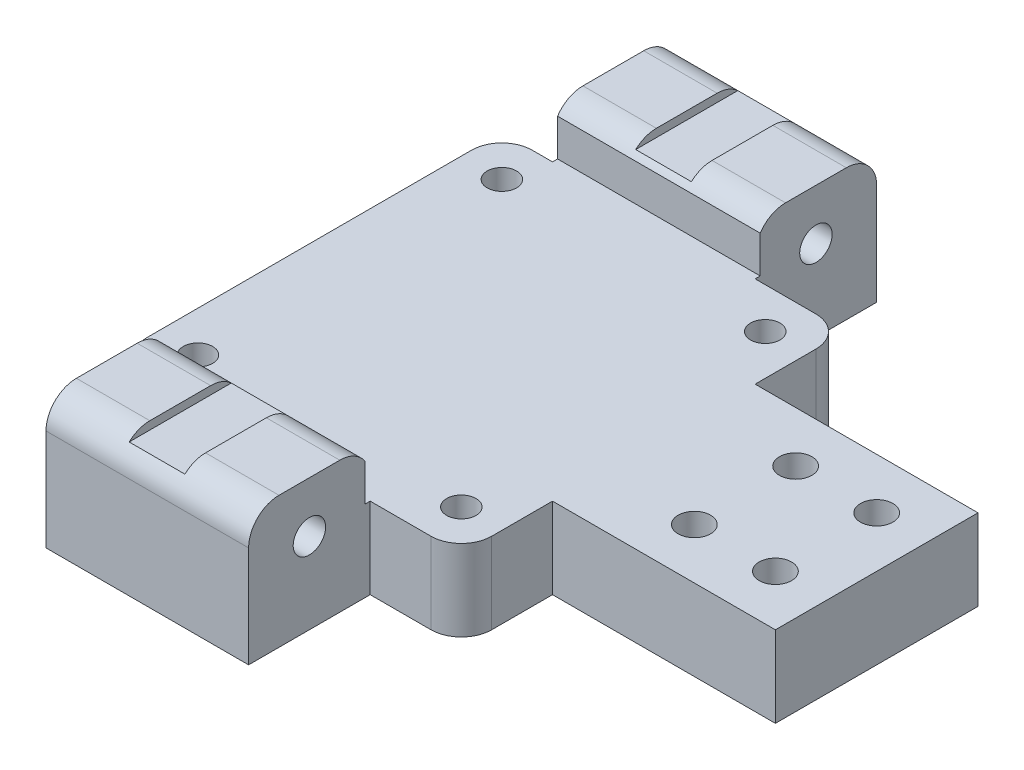
SolidWorks part; units mm, degrees
ref_plane "Front" through (0, 0, 0) normal (0, 0, 1) x (1, 0, 0)
ref_plane "Top" through (0, 0, 0) normal (0, 1, 0) x (1, 0, 0)
ref_plane "Right" through (0, 0, 0) normal (1, 0, 0) x (0, 0, -1)
sketch "Sketch1" plane through (0, 0, 0) normal (0, 1, 0) x (1, 0, 0)
  line L1 (0, 0) -> (300, 0)
  line L2 (0, 0) -> (0, -20)
  line L3 (0, -20) -> (300, -20)
  line L4 (300, 0) -> (300, -20)
  dimension "D1" = 20
  dimension "D2" = 300
extrude "Boss-Extrude1" add sketch "Sketch1" along normal blind 8
sketch "Sketch2" plane through (0, 0, 20) normal (0, 0, 1) x (1, 0, 0)
  line L0 (0, 8) -> (300, 8) construction
  line L1 (0, 0) -> (34, 0)
  line L2 (0, 0) -> (0, 8)
  line L3 (0, 8) -> (34, 8)
  line L4 (34, 0) -> (34, 8)
  line L5 (266, 8) -> (300, 8)
  line L6 (300, 0) -> (300, 8)
  line L7 (266, 0) -> (300, 0)
  line L8 (266, 0) -> (266, 8)
  dimension "D1" = 34
  dimension "D2" = 2
extrude "Boss-Extrude2" add sketch "Sketch2" along normal blind 9
sketch "Sketch3" plane through (0, 0, 0) normal (0, 0, -1) x (-1, 0, 0)
  line L0 (-300, 8) -> (0, 8) construction
  line L1 (0, 0) -> (-34, 0)
  line L2 (0, 0) -> (0, 8)
  line L3 (0, 8) -> (-34, 8)
  line L4 (-34, 0) -> (-34, 8)
  line L5 (-300, 0) -> (-300, 8)
  line L6 (-266, 8) -> (-300, 8)
  line L7 (-266, 0) -> (-266, 8)
  line L8 (-266, 0) -> (-300, 0)
  dimension "D1" = 34
  dimension "D2" = 2
extrude "Boss-Extrude3" add sketch "Sketch3" along normal blind 9
sketch "Sketch4" plane through (0, 8, 0) normal (0, 1, 0) x (1, 0, 0)
  line L0 (0, 9) -> (34, 9) construction
  line L1 (0, 9) -> (0, -29) construction
  circle A0 centre (4, 5) radius 1.45
  circle A1 centre (30, 5) radius 1.45
  circle A2 centre (30, -25) radius 1.45
  circle A3 centre (4, -25) radius 1.45
  circle A4 centre (296, -25) radius 1.45
  circle A5 centre (296, 5) radius 1.45
  circle A6 centre (270, -25) radius 1.45
  circle A7 centre (270, 5) radius 1.45
  dimension "D1" = 2.9
  dimension "D2" = 4
  dimension "D3" = 4
  dimension "D4" = 2
  dimension "D5" = 2
  dimension "D6" = 2
extrude "Cut-Extrude1" cut sketch "Sketch4" against normal through all
sketch "Sketch5" plane through (0, 0, 20) normal (0, 0, 1) x (1, 0, 0)
  line L0 (34, 8) -> (266, 8) construction
  line L1 (266, 0) -> (241, 0)
  line L2 (266, 0) -> (266, 8)
  line L3 (266, 8) -> (241, 8)
  line L4 (241, 0) -> (241, 8)
  dimension "D1" = 25
extrude "Boss-Extrude4" add sketch "Sketch5" along normal blind 17
sketch "Sketch6" plane through (0, 0, 0) normal (0, 0, -1) x (-1, 0, 0)
  line L0 (-266, 0) -> (-34, 0) construction
  line L1 (-266, 8) -> (-241, 8)
  line L2 (-266, 8) -> (-266, 0)
  line L3 (-266, 0) -> (-241, 0)
  line L4 (-241, 8) -> (-241, 0)
  dimension "D1" = 25
extrude "Boss-Extrude5" add sketch "Sketch6" along normal blind 17
sketch "Sketch7" plane through (0, 8, 0) normal (0, 1, 0) x (1, 0, 0)
  line L0 (266, -37) -> (241, -37) construction
  line L1 (259, -29) -> (249, -29)
  line L2 (259, -29) -> (259, 9)
  line L3 (259, 9) -> (249, 9)
  line L4 (249, -29) -> (249, 9)
  line L5 (241, -37) -> (241, -20) construction
  dimension "D1" = 10
  dimension "D2" = 38
  dimension "D3" = 8
  dimension "D4" = 8
extrude "Cut-Extrude2" cut sketch "Sketch7" against normal through all
sketch "Sketch8" plane through (0, 8, 0) normal (0, 1, 0) x (1, 0, 0)
  line L0 (259, -29) -> (259, 9) construction
  line L1 (259, -18) -> (266, -18)
  line L2 (259, -18) -> (259, -2)
  line L3 (259, -2) -> (266, -2)
  line L4 (266, -18) -> (266, -2)
  line L5 (266, -37) -> (241, -37) construction
  dimension "D1" = 7
  dimension "D2" = 16
  dimension "D3" = 19
extrude "Cut-Extrude3" cut sketch "Sketch8" against normal blind 4
sketch "Sketch9" plane through (259, 0, 0) normal (-1, 0, 0) x (0, 0, 1)
  line L0 (18, 4) -> (22, 8)
  line L1 (29, 8) -> (18, 8) construction
  line L2 (22, 8) -> (18, 8)
  line L3 (18, 8) -> (18, 4)
  line L4 (2, 4) -> (-2, 8)
  line L5 (2, 8) -> (-9, 8) construction
  line L6 (-2, 8) -> (2, 8)
  line L7 (2, 8) -> (2, 4)
  dimension "D1" = 4
  dimension "D2" = 4
extrude "Cut-Extrude4" cut sketch "Sketch9" against normal blind 7
sketch "Sketch10" plane through (259, 0, 0) normal (-1, 0, 0) x (0, 0, 1)
  line L0 (-9, 8) -> (-2, 0)
  line L1 (29, 0) -> (-9, 0) construction
  line L2 (-2, 0) -> (-9, 0)
  line L3 (-9, 0) -> (-9, 8)
  line L4 (29, 8) -> (22, 0)
  line L5 (22, 0) -> (29, 0)
  line L6 (29, 0) -> (29, 8)
  line L7 (-51.4523, 12.1971) -> (-51.8778, 12.5861)
  line M6 (-9, 8) -> (-9, 0)
  line M7 (-9, 0) -> (29, 0)
  line M8 (29, 0) -> (29, 8)
  dimension "D1" = 7
  dimension "D2" = 7
extrude "Boss-Extrude6" add sketch "Sketch10" along normal blind 10 contours L0 M6 M7 | L4 M8 M7
sketch "Sketch12" plane through (0, 0, 37) normal (0, 0, 1) x (1, 0, 0)
  line L0 (241, 0) -> (266, 0) construction
  line L1 (241, 8) -> (249, 8)
  line L2 (241, 8) -> (241, 0)
  line L3 (241, 0) -> (249, 0)
  line L4 (249, 8) -> (249, 0)
  dimension "D1" = 8
extrude "Boss-Extrude7" add sketch "Sketch12" along normal blind 17
sketch "Sketch13" plane through (0, 8, 0) normal (0, 1, 0) x (1, 0, 0)
  line L0 (249, -54) -> (241, -54) construction
  line L1 (249, -54) -> (249, -37) construction
  circle A0 centre (245, -50) radius 1.7
  circle A1 centre (245, -18) radius 1.7
  dimension "D1" = 3.4
  dimension "D2" = 4
  dimension "D3" = 4
  dimension "D4" = 2
extrude "Cut-Extrude6" cut sketch "Sketch13" against normal through all
sketch "Sketch14" plane through (0, 0, 29) normal (0, 0, 1) x (1, 0, 0)
  line L1 (295, 13) -> (275, 13)
  line L2 (295, 13) -> (295, 0)
  line L3 (295, 0) -> (275, 0)
  line L4 (275, 13) -> (275, 0)
  line L5 (266, 0) -> (300, 0) construction
  line L7 (266, 8) -> (266, 0) construction
  dimension "D1" = 20
  dimension "D2" = 9
  dimension "D3" = 13
extrude "Boss-Extrude8" add sketch "Sketch14" along normal blind 12
sketch "Sketch15" plane through (295, 0, 0) normal (1, 0, 0) x (0, 0, -1)
  line L0 (-41, 0) -> (-41, 13) construction
  line L1 (-41, 13) -> (-29, 13) construction
  circle A0 centre (-35, 8) radius 1.6
  dimension "D1" = 3.2
  dimension "D2" = 6
  dimension "D3" = 5
extrude "Cut-Extrude7" cut sketch "Sketch15" against normal blind 20
sketch "Sketch16" plane through (0, 0, -9) normal (0, 0, -1) x (-1, 0, 0)
  line L1 (-295, 13) -> (-275, 13)
  line L2 (-295, 13) -> (-295, 0)
  line L3 (-295, 0) -> (-275, 0)
  line L4 (-275, 13) -> (-275, 0)
  line L5 (-300, 0) -> (-266, 0) construction
  line L6 (-266, 0) -> (-266, 8) construction
  dimension "D1" = 20
  dimension "D2" = 9
  dimension "D3" = 13
extrude "Boss-Extrude9" add sketch "Sketch16" along normal blind 12
sketch "Sketch17" plane through (295, 0, 0) normal (1, 0, 0) x (0, 0, -1)
  line L1 (21, 13) -> (21, 0) construction
  line L2 (21, 13) -> (9, 13) construction
  circle A0 centre (15, 8) radius 1.6
  dimension "D1" = 3.2
  dimension "D2" = 5
  dimension "D3" = 6
extrude "Cut-Extrude8" cut sketch "Sketch17" against normal blind 20
sketch "Sketch18" plane through (0, 0, -9) normal (0, 0, -1) x (-1, 0, 0)
  line L1 (-25, 13) -> (-5, 13)
  line L2 (-25, 13) -> (-25, 0)
  line L3 (-25, 0) -> (-5, 0)
  line L4 (-5, 13) -> (-5, 0)
  line L5 (-34, 0) -> (0, 0) construction
  line L6 (-34, 8) -> (-34, 0) construction
  dimension "D1" = 20
  dimension "D2" = 9
  dimension "D3" = 13
extrude "Boss-Extrude10" add sketch "Sketch18" along normal blind 12
sketch "Sketch19" plane through (5, 0, 0) normal (-1, 0, 0) x (0, 0, 1)
  line L0 (-21, 0) -> (-21, 13) construction
  line L1 (-21, 13) -> (-9, 13) construction
  circle A0 centre (-15, 8) radius 1.6
  dimension "D1" = 3.2
  dimension "D2" = 6
  dimension "D3" = 5
extrude "Cut-Extrude9" cut sketch "Sketch19" against normal blind 20
sketch "Sketch20" plane through (0, 0, 29) normal (0, 0, 1) x (1, 0, 0)
  line L1 (5, 13) -> (25, 13)
  line L2 (5, 13) -> (5, 0)
  line L3 (5, 0) -> (25, 0)
  line L4 (25, 13) -> (25, 0)
  line L5 (0, 0) -> (34, 0) construction
  line L6 (34, 0) -> (34, 8) construction
  dimension "D1" = 20
  dimension "D2" = 9
  dimension "D3" = 13
extrude "Boss-Extrude11" add sketch "Sketch20" along normal blind 12
sketch "Sketch21" plane through (5, 0, 0) normal (-1, 0, 0) x (0, 0, 1)
  line L0 (41, 13) -> (41, 0) construction
  line L2 (41, 13) -> (29, 13) construction
  circle A0 centre (35, 8) radius 1.6
  dimension "D1" = 3.2
  dimension "D2" = 6
  dimension "D3" = 5
extrude "Cut-Extrude10" cut sketch "Sketch21" against normal blind 20
fillet "Fillet6" radius 3 8 edges at (15, 13, 41) (15, 13, 29) (15, 13, -9) (15, 13, -21) (285, 13, 41) (285, 13, 29) (285, 13, -9) (285, 13, -21)
sketch "Sketch22" plane through (300, 0, 0) normal (1, 0, 0) x (0, 0, -1)
  line L1 (-72.0035, 35.0177) -> (51.7473, 35.0177)
  line L2 (-72.0035, 35.0177) -> (-72.0035, -37.6215)
  line L3 (-72.0035, -37.6215) -> (51.7473, -37.6215)
  line L4 (51.7473, 35.0177) -> (51.7473, -37.6215)
extrude "Cut-Extrude11" cut sketch "Sketch22" against normal blind 244
sketch "Sketch23" plane through (0, 0, 0) normal (0, -1, 0) x (-1, 0, 0)
  line L0 (-34, -20) -> (-56, -20) construction
  line L1 (-56, -20) -> (-56, 0) construction
  line L2 (-56, 0) -> (-34, 0) construction
  circle A0 centre (-51, -5) radius 1.6
  circle A1 centre (-51, -15) radius 1.6
  circle A2 centre (-43, -5) radius 1.6
  circle A3 centre (-43, -15) radius 1.6
  dimension "D1" = 3.2
  dimension "D2" = 3.2
  dimension "D3" = 3.2
  dimension "D4" = 3.2
  dimension "D5" = 5
  dimension "D6" = 5
  dimension "D7" = 5
  dimension "D8" = 5
  dimension "D9" = 5
  dimension "D10" = 8
  dimension "D11" = 8
  dimension "D12" = 5
extrude "Cut-Extrude12" cut sketch "Sketch23" against normal through all
fillet "Fillet7" radius 3 4 edges at (0, 4, 29) (0, 4, -9) (34, 4, 29) (34, 4, -9)
sketch "Sketch24" plane through (0, 13, 0) normal (0, 1, 0) x (1, 0, 0)
  line L0 (5, 18) -> (5, 12) construction
  line L1 (12.25, 29.5448) -> (17.75, 29.5448)
  line L2 (12.25, 29.5448) -> (12.25, -48.6988)
  line L3 (12.25, -48.6988) -> (17.75, -48.6988)
  line L4 (17.75, 29.5448) -> (17.75, -48.6988)
  dimension "D1" = 5.5
  dimension "D2" = 7.25
extrude "Cut-Extrude13" cut sketch "Sketch24" against normal blind 0.8
sketch "Sketch25" plane through (0, 0, 29) normal (0, 0, -1) x (-1, 0, 0)
  line L1 (-25, 8) -> (-5, 8)
  line L2 (-25, 8) -> (-25, 13.7566)
  line L3 (-25, 13.7566) -> (-5, 13.7566)
  line L4 (-5, 8) -> (-5, 13.7566)
  dimension "D1" = 20
extrude "Cut-Extrude14" cut sketch "Sketch25" against normal blind 0.5
sketch "Sketch26" plane through (0, 0, -9) normal (0, 0, 1) x (1, 0, 0)
  line L1 (5, 8) -> (25, 8)
  line L2 (5, 8) -> (5, 29.4591)
  line L3 (5, 29.4591) -> (25, 29.4591)
  line L4 (25, 8) -> (25, 29.4591)
  dimension "D1" = 20
extrude "Cut-Extrude15" cut sketch "Sketch26" against normal blind 0.5
